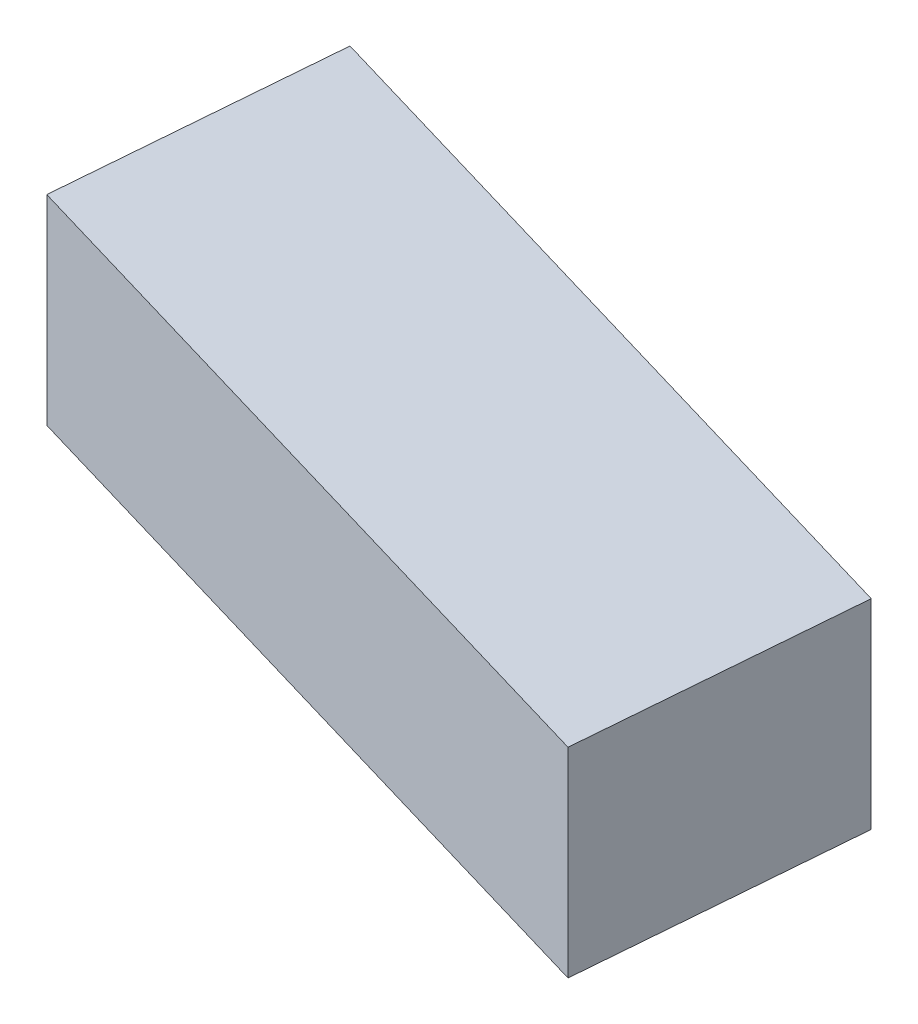
SolidWorks part; units mm, degrees
ref_plane "Front Plane" through (0, 0, 0) normal (0, 0, 1) x (1, 0, 0)
ref_plane "Top Plane" through (0, 0, 0) normal (0, 1, 0) x (1, 0, 0)
ref_plane "Right Plane" through (0, 0, 0) normal (1, 0, 0) x (0, 0, -1)
sketch "Sketch2" plane through (0, 0, 0) normal (0, 1, 0) x (1, 0, 0)
  line L0 (-68.6499, 31.038) -> (-72.412, -14.9143)
  line L5 (-68.6499, 31.038) -> (52.5459, -4.7027)
  line L6 (-72.412, -14.9143) -> (48.7838, -50.655)
  line L7 (52.5459, -4.7027) -> (48.7838, -50.655)
extrude "Boss-Extrude2" add sketch "Sketch2" along normal blind 32.766 contours L0 L5 L7 L6
